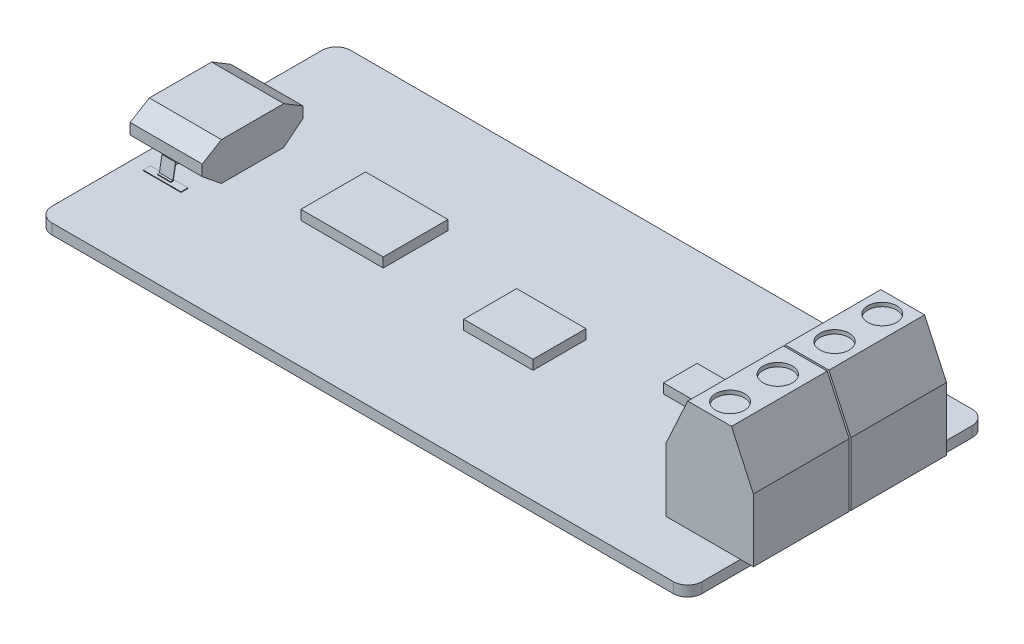
SolidWorks part; units mm, degrees
ref_plane "Front Plane" through (0, 0, 0) normal (0, 0, 1) x (1, 0, 0)
ref_plane "Top Plane" through (0, 0, 0) normal (0, 1, 0) x (1, 0, 0)
ref_plane "Right Plane" through (0, 0, 0) normal (1, 0, 0) x (0, 0, -1)
sketch "Sketch1" plane through (0, 0, 0) normal (0, 1, 0) x (1, 0, 0)
  line L0 (13.55, 7.635) -> (-13.55, -7.635) construction
  line L1 (-13.55, 7.635) -> (11.83, 7.635)
  line L2 (-13.55, 7.635) -> (-13.55, -7.635)
  line L4 (13.55, 7.635) -> (13.55, -7.635) construction
  line L5 (11.83, 28.3243) -> (11.83, -30.9439) construction
  line L6 (11.83, 3.675) -> (13.55, 2.295)
  line L7 (-13.55, 0) -> (13.55, 0) construction
  line L8 (11.83, 3.675) -> (11.83, 7.635)
  line L9 (11.83, 7.635) -> (13.55, 7.635) construction
  line L10 (-13.55, -7.635) -> (11.83, -7.635)
  line L11 (11.83, -7.635) -> (13.55, -7.635) construction
  line L12 (11.83, -3.675) -> (11.83, -7.635)
  line L13 (11.83, -3.675) -> (13.55, -2.295)
  line L14 (13.55, 2.295) -> (13.55, -2.295)
  point P7 (11.83, 3.675)
  point P8 (13.55, 2.295)
  dimension "D1" = 15.27
  dimension "D2" = 27.1
  dimension "D3" = 1.72
  dimension "D4" = 3.96
  dimension "D5" = 5.34
extrude "Boss-Extrude1" add sketch "Sketch1" along normal mid plane 0.81
fillet "Fillet1" radius 1.12 2 edges at (-13.55, 0, -7.635) (-13.55, 0, 7.635)
chamfer "Chamfer1" distance 0.5 angle 45 2 edges at (11.83, 0, 7.635) (11.83, 0, -7.635)
sketch "Sketch2" plane through (0, 0.405, 0) normal (0, 1, 0) x (1, 0, 0)
  line L0 (-13.55, 0) -> (13.55, 0) construction
  line L1 (-13.55, 6.515) -> (-13.55, -6.515) construction
  line L2 (13.55, -2.295) -> (13.55, 2.295) construction
  line L3 (9.57, 5.74) -> (9.57, 6.84) construction
  line L4 (9.57, 5.74) -> (9.57, -5.74) construction
  line L5 (9.57, -5.74) -> (9.57, -6.84) construction
  line L6 (9.57, 5.74) -> (10.67, 5.74) construction
  circle A0 centre (9.57, 5.74) radius 1.1
  circle A1 centre (9.57, -5.74) radius 1.1
  point P10 (9.57, 0)
  dimension "D1" = 2.2
  dimension "D2" = 13.68
  dimension "D3" = 2.88
extrude "Cut-Extrude1" cut sketch "Sketch2" against normal through all
sketch "Sketch3" plane through (-13.55, 0, 0) normal (-1, 0, 0) x (0, 0, 1)
  line L0 (-3.91, 1.655) -> (-2.42, 0.455)
  line L1 (-2.42, 3.405) -> (2.42, 3.405)
  line L2 (-2.42, 3.405) -> (-2.42, 0.455) construction
  line L3 (-2.42, 0.455) -> (2.42, 0.455)
  line L4 (2.42, 3.405) -> (2.42, 0.455) construction
  line L5 (-3.91, 2.505) -> (-2.42, 3.405)
  line L6 (-3.91, 2.505) -> (-3.91, 1.655)
  line L7 (0, 3.405) -> (0, 0.455) construction
  line L8 (3.91, 1.655) -> (2.42, 0.455)
  line L9 (3.91, 2.505) -> (2.42, 3.405)
  line L10 (3.91, 2.505) -> (3.91, 1.655)
  line L11 (0, 0) -> (0, 0.455) construction
  line L12 (-6.515, 0.405) -> (6.515, 0.405) construction
  point P10 (0, 1.93)
  dimension "D1" = 2.95
  dimension "D2" = 7.82
  dimension "D3" = 0.9
  dimension "D4" = 1.2
  dimension "D5" = 4.84
  dimension "D6" = 0.05
extrude "Boss-Extrude2" add sketch "Sketch3" along normal blind 0.5 and the other way blind 5.1 separate body
sketch "Sketch4" plane through (0, 0.405, 0) normal (0, 1, 0) x (1, 0, 0)
  line L0 (0, 0) -> (-16.5807, 0) construction
  line L1 (-12.4018, 4.55) -> (-9.46, 4.55)
  line L2 (-12.4018, 4.55) -> (-12.4018, 4.0002)
  line L3 (-12.4018, 4.0002) -> (-9.46, 4.0002)
  line L4 (-9.46, 4.55) -> (-9.46, 4.0002)
  line L5 (-9.46, -4.55) -> (-9.46, -4.0002)
  line L6 (-12.4018, -4.0002) -> (-9.46, -4.0002)
  line L7 (-12.4018, -4.55) -> (-12.4018, -4.0002)
  line L8 (-12.4018, -4.55) -> (-9.46, -4.55)
extrude "Boss-Extrude3" add sketch "Sketch4" along normal blind 0.05
ref_plane "Plane1" through (-11, 0, 0) normal (1, 0, 0) x (0, 0, -1)
sketch "Sketch5" plane through (-11, 0, 0) normal (1, 0, 0) x (0, 0, -1)
  line L0 (4.3254, 0.455) -> (4.3254, 0.5094)
  line L1 (4.55, 0.455) -> (4.0002, 0.455) construction
  line L2 (4.3254, 0.5094) -> (4.1621, 0.5094)
  line L3 (4.1621, 0.5094) -> (3.9644, 1.6441)
  line L4 (3.9644, 1.6441) -> (3.4984, 1.6441)
  line L5 (3.4984, 1.6441) -> (3.4984, 1.4426)
  line L6 (3.4984, 1.4426) -> (3.9644, 1.4426)
  line L7 (3.9644, 1.4426) -> (4.1365, 0.455)
  line L8 (4.1365, 0.455) -> (4.3254, 0.455)
  line L9 (0, 0) -> (0, 5.4291) construction
  line L10 (-4.1365, 0.455) -> (-4.3254, 0.455)
  line L11 (-3.9644, 1.4426) -> (-4.1365, 0.455)
  line L12 (-3.4984, 1.4426) -> (-3.9644, 1.4426)
  line L13 (-3.4984, 1.6441) -> (-3.4984, 1.4426)
  line L14 (-3.9644, 1.6441) -> (-3.4984, 1.6441)
  line L15 (-4.1621, 0.5094) -> (-3.9644, 1.6441)
  line L16 (-4.3254, 0.5094) -> (-4.1621, 0.5094)
  line L17 (-4.3254, 0.455) -> (-4.3254, 0.5094)
extrude "Boss-Extrude4" add sketch "Sketch5" along normal mid plane 1.05
sketch "Sketch6" plane through (0, 0.405, 0) normal (0, 1, 0) x (1, 0, 0)
  line L0 (13.55, 0) -> (-14.05, 0) construction
  line L1 (13.55, -2.295) -> (13.55, 2.295) construction
  line L2 (-14.05, -2.42) -> (-14.05, 2.42) construction
  line L3 (-5.9852, 5.9137) -> (-3.7107, 5.9137) construction
  circle A0 centre (-5.9852, 5.9137) radius 0.5776
  circle A1 centre (-3.4852, 5.9137) radius 0.5776
  circle A2 centre (-0.9852, 5.9137) radius 0.5776
  circle A3 centre (1.5148, 5.9137) radius 0.5776
  circle A4 centre (4.0148, 5.9137) radius 0.5776
  circle A5 centre (4.0148, -5.9137) radius 0.5776
  circle A6 centre (1.5148, -5.9137) radius 0.5776
  circle A7 centre (-0.9852, -5.9137) radius 0.5776
  circle A8 centre (-3.4852, -5.9137) radius 0.5776
  circle A9 centre (-5.9852, -5.9137) radius 0.5776
  dimension "D1" = 5
extrude "Cut-Extrude2" cut sketch "Sketch6" against normal through all
sketch "Sketch7" plane through (0, 0.405, 0) normal (0, 1, 0) x (1, 0, 0)
  line L0 (-7.8408, 7.635) -> (36.95, 7.635) construction
  line L1 (11.33, 7.635) -> (-12.43, 7.635) construction
  line L2 (36.95, 7.635) -> (36.95, -7.8839) construction
  line L3 (36.95, -7.8839) -> (-7.8408, -7.8839) construction
  line L4 (-7.8408, -7.8839) -> (-7.8408, 7.635) construction
  line L5 (-13.55, 6.515) -> (-13.55, -6.515) construction
  line L6 (36.95, 11.605) -> (36.95, -11.605)
  line L7 (0, 0) -> (36.95, 0) construction
  line L8 (36.95, 11.605) -> (-13.55, 11.605)
  line L9 (-13.55, 11.605) -> (-13.55, -11.605)
  line L10 (-13.55, -11.605) -> (36.95, -11.605)
  point P13 (0, 0)
  point P16 (0, 0)
  dimension "D1" = 50.5
  dimension "D2" = 23.21
extrude "Boss-Extrude5" add sketch "Sketch7" against normal up to vertex (0.81 mm away) up to point (11.83, -0.405, -7.135)
fillet "Fillet2" radius 1.12 4 edges at (36.95, 0, 11.605) (36.95, 0, -11.605) (-13.55, 0, 11.605) (-13.55, 0, -11.605)
sketch "Sketch8" plane through (0, 0.405, 0) normal (0, 1, 0) x (1, 0, 0)
  line L1 (-2.9269, 3.2539) -> (3.4741, 3.2539)
  line L2 (-2.9269, 3.2539) -> (-2.9269, -1.7755)
  line L3 (-2.9269, -1.7755) -> (3.4741, -1.7755)
  line L4 (3.4741, 3.2539) -> (3.4741, -1.7755)
  line L5 (10.7896, 1.2726) -> (16.1746, 1.2726)
  line L6 (10.7896, 1.2726) -> (10.7896, -2.8424)
  line L7 (10.7896, -2.8424) -> (16.1746, -2.8424)
  line L8 (16.1746, 1.2726) -> (16.1746, -2.8424)
  line L9 (22.8296, 3.2539) -> (26.7921, 3.2539)
  line L10 (22.8296, 3.2539) -> (22.8296, 0.6363)
  line L11 (22.8296, 0.6363) -> (26.7921, 0.6363)
  line L12 (26.7921, 3.2539) -> (26.7921, 0.6363)
  point P12 (16.1746, -2.8424)
extrude "Boss-Extrude6" add sketch "Sketch8" along normal blind 0.75
sketch "Sketch9" plane through (0, 0, 0) normal (0, 0, 1) x (1, 0, 0)
  line L0 (37.95, 0.405) -> (37.95, 5.305)
  line L1 (37.95, 5.305) -> (36.25, 9.005)
  line L2 (36.25, 9.005) -> (32.85, 9.005)
  line L3 (32.85, 9.005) -> (31.15, 5.305)
  line L4 (31.15, 5.305) -> (31.15, 0.405)
  line L5 (31.15, 0.405) -> (37.95, 0.405)
  line L6 (-12.43, 0.405) -> (35.83, 0.405) construction
  line L8 (31.15, 5.305) -> (37.95, 5.305) construction
  line L9 (34.55, 9.005) -> (34.55, 0.405) construction
  line L11 (36.95, 0.405) -> (36.95, -0.405) construction
  point P8 (0, 0)
  point P9 (0, 0)
  point P10 (0, 0)
  point P13 (36.6233, 9.005)
  point P14 (32.5208, 9.005)
  point P15 (32.2474, 9.005)
  point P16 (0, 0)
  point P19 (0, 0)
  dimension "D1" = 3.4
  dimension "D2" = 6.8
  dimension "D3" = 1
  dimension "D4" = 4.9
  dimension "D5" = 8.6
extrude "Boss-Extrude7" add sketch "Sketch9" along normal mid plane 15
sketch "Sketch10" plane through (37.95, 0, 0) normal (1, 0, 0) x (0, 0, -1)
  line L0 (0, 0) -> (0, 0.405) construction
  line L1 (-0.0663, 11.4794) -> (0.0663, 11.4794)
  line L2 (-0.0663, 11.4794) -> (-0.0663, 0.405)
  line L3 (-0.0663, 0.405) -> (0.0663, 0.405)
  line L4 (0.0663, 11.4794) -> (0.0663, 0.405)
  line L5 (-10.485, 0.405) -> (-7.5, 0.405) construction
  point P7 (0, 0)
extrude "Cut-Extrude3" cut sketch "Sketch10" against normal up to vertex (6.8 mm away) up to point (31.15, 5.305, -7.5)
sketch "Sketch11" plane through (0, 9.005, 0) normal (0, 1, 0) x (1, 0, 0)
  line L0 (31.15, 0.0663) -> (31.15, -0.0663) construction
  line L1 (31.15, 0) -> (41.1316, 0) construction
  line L2 (34.55, 5.9101) -> (34.55, -5.9101) construction
  line L3 (36.25, -5.066) -> (32.85, -5.066) construction
  line L4 (36.25, -7.5) -> (36.25, -0.0663) construction
  line L5 (32.85, -7.5) -> (32.85, -0.0663) construction
  circle A0 centre (34.55, 5.9101) radius 1.1233
  circle A1 centre (34.55, 2.2057) radius 1.1364
  circle A2 centre (34.55, -2.2057) radius 1.1364
  circle A3 centre (34.55, -5.9101) radius 1.1233
  point P21 (34.55, -5.066)
  point P22 (0, 0)
  point P23 (34.55, -2.2057)
  point P24 (34.55, -5.9101)
extrude "Cut-Extrude4" cut sketch "Sketch11" against normal blind 0.3
